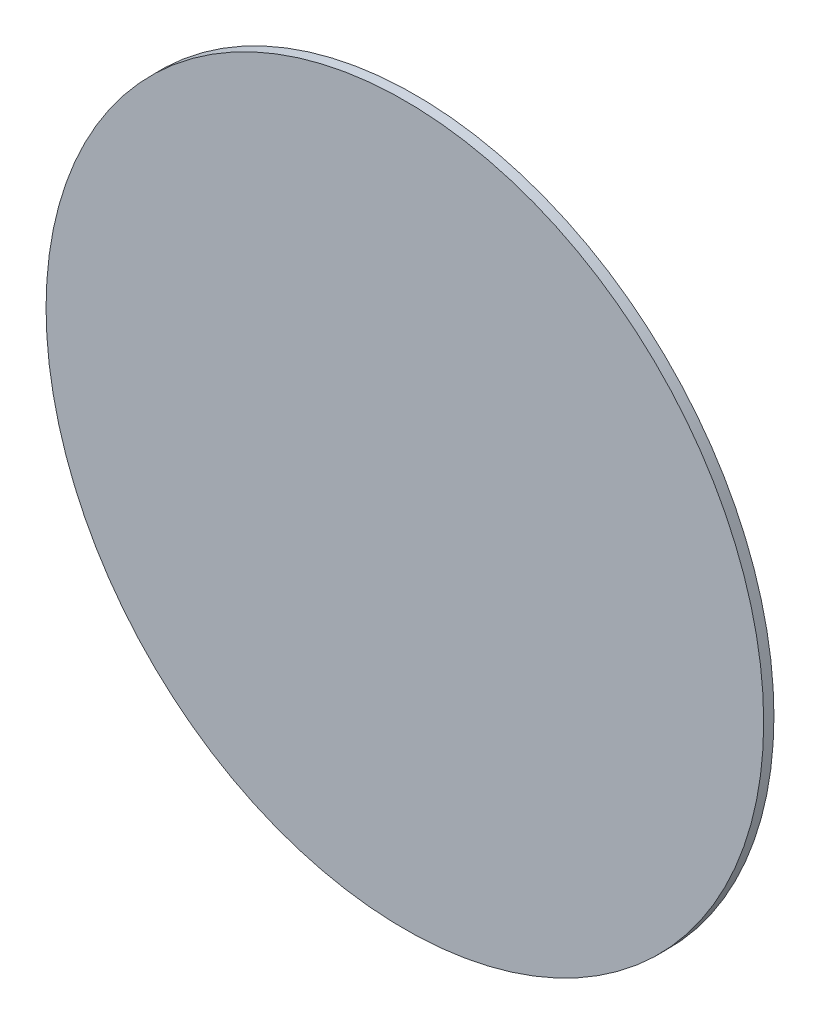
SolidWorks part; units mm, degrees
ref_plane "Front Plane" through (0, 0, 0) normal (0, 0, 1) x (1, 0, 0)
ref_plane "Top Plane" through (0, 0, 0) normal (0, 1, 0) x (1, 0, 0)
ref_plane "Right Plane" through (0, 0, 0) normal (1, 0, 0) x (0, 0, -1)
sketch "Sketch1" plane through (0, 0, 0) normal (0, 0, 1) x (1, 0, 0)
  circle A0 centre (0, 0) radius 70
  dimension "D1" = 140
extrude "Boss-Extrude1" add sketch "Sketch1" along normal blind 2
